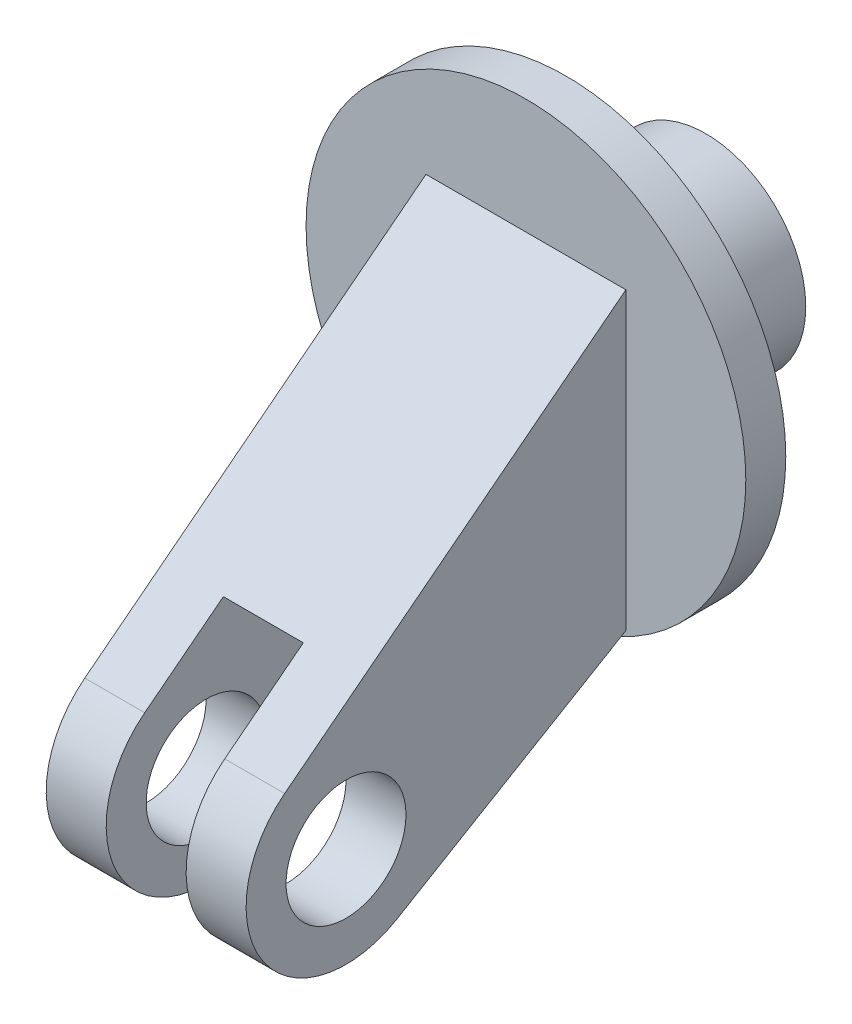
SolidWorks part; units mm, degrees
ref_plane "up基准面" through (0, 0, 0) normal (0, 0, 1) x (1, 0, 0)
ref_plane "前基准面" through (0, 0, 0) normal (0, 1, 0) x (1, 0, 0)
ref_plane "右视基准面" through (0, 0, 0) normal (1, 0, 0) x (0, 0, -1)
sketch "草图1" plane through (0, 0, 0) normal (0, 0, 1) x (1, 0, 0)
  circle A0 centre (0, 0) radius 55
extrude "凸台-拉伸1" add sketch "草图1" along normal blind 10
sketch "草图2" plane through (0, 0, 0) normal (0, 0, -1) x (-1, 0, 0)
  circle A0 centre (0, 0) radius 25
extrude "凸台-拉伸2" add sketch "草图2" along normal blind 35
sketch "草图3" plane through (0, 0, 0) normal (1, 0, 0) x (0, 0, -1)
  line L0 (-10, -47.6567) -> (-10, 26.1722)
  line L2 (-67.2767, -81.5202) -> (-10, -47.6567)
  line L3 (-95.3566, -40.2725) -> (-10, 26.1722)
  line L4 (-10, 26.1722) -> (-10, 55)
  circle A0 centre (-80, -60) radius 25
  circle A1 centre (-80, -60) radius 15
  dimension "D1" = 50
  dimension "D2" = 30
  dimension "D3" = 60
  dimension "D4" = 80
extrude "凸台-拉伸3" add sketch "草图3" along normal mid plane 50 contours A0 L2 L0 L3 | A0 A1
sketch "草图6" plane through (0, 0, 0) normal (1, 0, 0) x (0, 0, -1)
  circle A0 centre (-80, -60) radius 35.3027
extrude "切除-拉伸2" cut sketch "草图6" against normal mid plane 20
